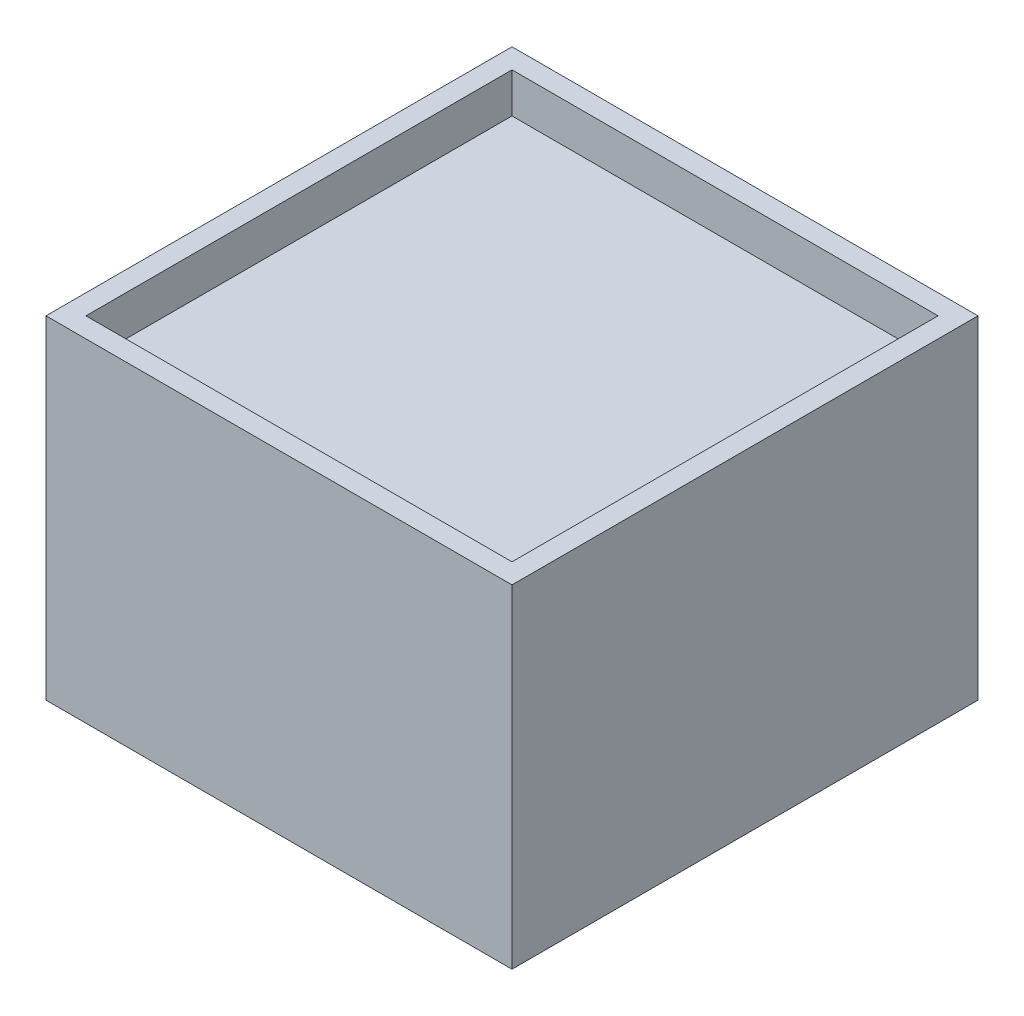
SolidWorks part; units mm, degrees
ref_plane "前视基准面" through (0, 0, 0) normal (0, 0, 1) x (1, 0, 0)
ref_plane "上视基准面" through (0, 0, 0) normal (0, 1, 0) x (1, 0, 0)
ref_plane "右视基准面" through (0, 0, 0) normal (1, 0, 0) x (0, 0, -1)
sketch "草图1" plane through (0, 0, 0) normal (0, 1, 0) x (1, 0, 0)
  line L1 (-17.5, 17.5) -> (17.5, 17.5)
  line L2 (-17.5, 17.5) -> (-17.5, -17.5)
  line L3 (-17.5, -17.5) -> (17.5, -17.5)
  line L4 (17.5, 17.5) -> (17.5, -17.5)
  line L5 (-17.5, 17.5) -> (17.5, -17.5) construction
  line L6 (-17.5, -17.5) -> (17.5, 17.5) construction
  point P0 (0, 0)
  dimension "D1" = 35
extrude "凸台-拉伸1" add sketch "草图1" along normal blind 25
sketch "草图2" plane through (0, 25, 0) normal (0, 1, 0) x (1, 0, 0)
  line L1 (-16, 16) -> (16, 16)
  line L2 (-16, 16) -> (-16, -16)
  line L3 (-16, -16) -> (16, -16)
  line L4 (16, 16) -> (16, -16)
  line L5 (-16, 16) -> (16, -16) construction
  line L6 (-16, -16) -> (16, 16) construction
  point P0 (0, 0)
  dimension "D1" = 32
  dimension "D2" = 32
extrude "切除-拉伸1" cut sketch "草图2" against normal blind 3
